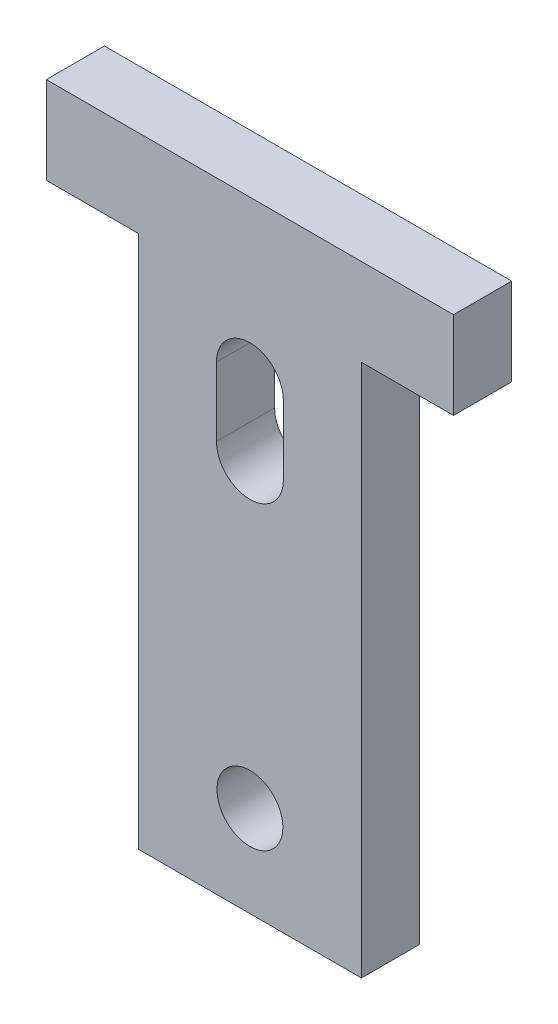
SolidWorks part; units mm, degrees
ref_plane "Front Plane" through (0, 0, 0) normal (0, 0, 1) x (1, 0, 0)
ref_plane "Top Plane" through (0, 0, 0) normal (0, 1, 0) x (1, 0, 0)
ref_plane "Right Plane" through (0, 0, 0) normal (1, 0, 0) x (0, 0, -1)
sketch "Sketch1" plane through (0, 0, 0) normal (0, 0, 1) x (1, 0, 0)
  line L0 (0, 12.6282) -> (0, -8.1465) construction
  line L1 (23.7298, 0) -> (-27.0782, 0) construction
  line L2 (10.5, 20.8535) -> (-10.5, 20.8535)
  line L3 (-10.5, 20.8535) -> (-10.5, 16.3535)
  line L4 (-10.5, 16.3535) -> (-5.75, 16.3535)
  line L5 (-5.75, 16.3535) -> (-5.75, -11.1465)
  line L6 (-5.75, -11.1465) -> (5.75, -11.1465)
  line L7 (5.75, 16.3535) -> (5.75, -11.1465)
  line L8 (10.5, 16.3535) -> (5.75, 16.3535)
  line L9 (10.5, 20.8535) -> (10.5, 16.3535)
  line L10 (0, 12.6282) -> (0, 9.0788) construction
  line L11 (1.7253, 12.6282) -> (1.7253, 9.0788)
  line L12 (-1.7253, 12.6282) -> (-1.7253, 9.0788)
  arc A1 (1.7253, 12.6282) -> (-1.7253, 12.6282) centre (0, 12.6282) ccw
  arc A2 (-1.7253, 9.0788) -> (1.7253, 9.0788) centre (0, 9.0788) ccw
  circle A3 centre (0, -6.4465) radius 1.7
  point P12 (0, -11.1465)
  point P15 (0, 20.8535)
  point P17 (0, 10.8535)
  point P24 (0, 7.3535)
  dimension "D5" = 7
  dimension "D6" = 4.7
  dimension "D7" = 6.5
  dimension "D1" = 11.5
  dimension "D2" = 32
  dimension "D3" = 4.5
  dimension "D4" = 21
  dimension "D8" = 12.1
extrude "Boss-Extrude1" add sketch "Sketch1" along normal blind 3 contours L6 L7 L8 L9 L2 L3 L4 L5
sketch "Sketch2" plane through (0, 0, 3) normal (0, 0, 1) x (1, 0, 0)
  line L0 (0, 22.0387) -> (0, -12.715) construction
  line L1 (-17.1639, 0) -> (24.9579, 0) construction
  line L5 (0, 12.6282) -> (0, 9.0788) construction
  line L13 (1.7253, 12.6282) -> (1.7253, 9.0788)
  line L14 (-1.7253, 12.6282) -> (-1.7253, 9.0788)
  line L15 (-5.75, -11.1465) -> (5.75, -11.1465) construction
  line L18 (10.5, 20.8535) -> (-10.5, 20.8535) construction
  circle A14 centre (0, -6.4465) radius 1.7
  arc A15 (1.7253, 12.6282) -> (-1.7253, 12.6282) centre (0, 12.6282) ccw
  arc A16 (-1.7253, 9.0788) -> (1.7253, 9.0788) centre (0, 9.0788) ccw
  point P7 (0, 10.8535)
  dimension "D2" = 6.5
  dimension "D1" = 4.7
extrude "Cut-Extrude1" cut sketch "Sketch2" against normal blind 3
